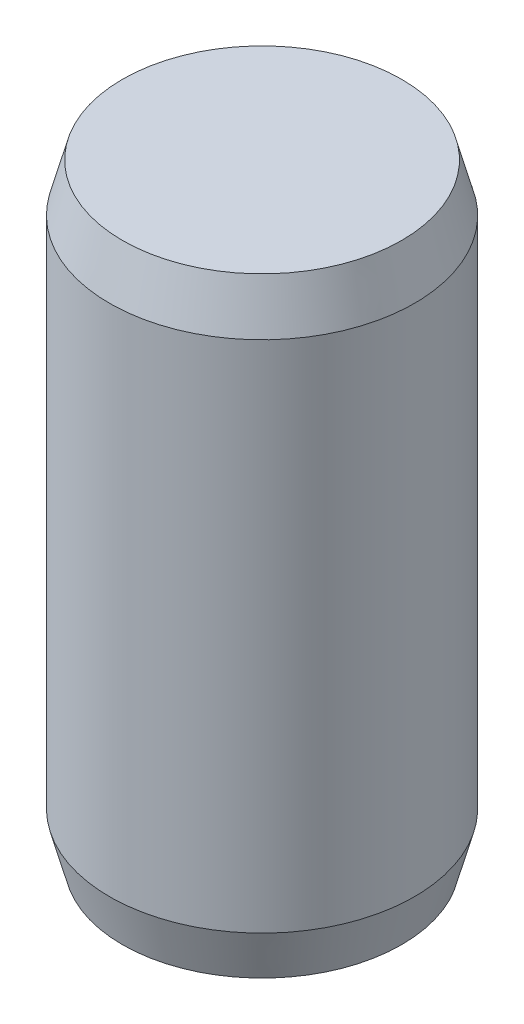
SolidWorks part; units mm, degrees
material "AISI 304"
ref_plane "前视基准面" through (0, 0, 0) normal (0, 0, 1) x (1, 0, 0)
ref_plane "上视基准面" through (0, 0, 0) normal (0, 1, 0) x (1, 0, 0)
ref_plane "右视基准面" through (0, 0, 0) normal (1, 0, 0) x (0, 0, -1)
sketch "草图1" plane through (0, 0, 0) normal (0, 0, 1) x (1, 0, 0)
  line L0 (0, -0.7094) -> (0, -1.0775) construction
  line L1 (0, 0) -> (2, 0) construction
  line L2 (0, -4) -> (2, -4)
  line L4 (0, 4) -> (2, 4)
  line L5 (2, -4) -> (2, 4)
  line L6 (0, -4) -> (0, 4)
  point P1 (0, 0)
  dimension "直径" = 4
  dimension "长度" = 8
revolve "旋转1" add sketch "草图1" angle 360 about L6
sketch "草图2" plane through (0, 0, 0) normal (0, 0, 1) x (1, 0, 0)
  line L1 (-2, -4) -> (2, -4) construction
  line L11 (0, 0) -> (0, -50000) construction
  line L16 (-2, -4) -> (2, -4) construction
  line L17 (1.8312, -4) -> (2, -3.37)
  line L18 (2, -4) -> (2, 4) construction
  line L19 (2, -3.37) -> (2.1, -3.37)
  line L20 (2.1, -3.37) -> (2.1, -4.1)
  line L21 (2.1, -4.1) -> (1.8312, -4.1)
  line L22 (1.8312, -4.1) -> (1.8312, -4)
  dimension "D1" = 0.1
  dimension "D2" = 0.1
  dimension "D3" = 15
  dimension "锥度长度" = 0.63
revolve "切除-旋转1" cut sketch "草图2" angle 360 about L11
mirror "镜向1" about plane through (0, 0, 0) normal (0, 1, 0) of "切除-旋转1"
